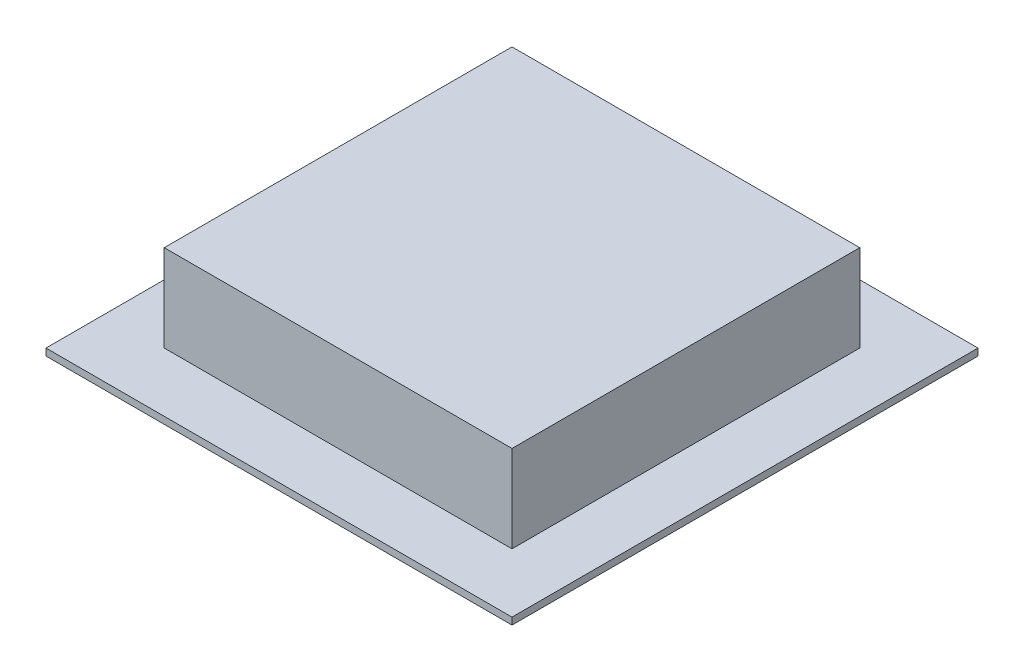
SolidWorks part; units mm, degrees
material "Default"
ref_plane "Front Plane" through (0, 0, 0) normal (0, 0, 1) x (1, 0, 0)
ref_plane "Top Plane" through (0, 0, 0) normal (0, 1, 0) x (1, 0, 0)
ref_plane "Right Plane" through (0, 0, 0) normal (1, 0, 0) x (0, 0, -1)
sketch "Sketch1" plane through (0, 0, 0) normal (0, 1, 0) x (1, 0, 0)
  line L1 (-85.09, 85.09) -> (85.09, 85.09)
  line L2 (-85.09, 85.09) -> (-85.09, -85.09)
  line L3 (-85.09, -85.09) -> (85.09, -85.09)
  line L4 (85.09, 85.09) -> (85.09, -85.09)
  point P4 (0, 85.09)
  point P6 (-85.09, 0)
  dimension "D1" = 170.18
  dimension "D2" = 170.18
extrude "Boss-Extrude1" add sketch "Sketch1" along normal blind 2.54
sketch "Sketch2" plane through (0, 2.54, 0) normal (0, 1, 0) x (1, 0, 0)
  line L1 (-63.5, 63.5) -> (63.5, 63.5)
  line L2 (-63.5, 63.5) -> (-63.5, -63.5)
  line L3 (-63.5, -63.5) -> (63.5, -63.5)
  line L4 (63.5, 63.5) -> (63.5, -63.5)
  point P4 (-63.5, 0)
  point P6 (0, 63.5)
  dimension "D1" = 127
  dimension "D2" = 127
extrude "Boss-Extrude2" add sketch "Sketch2" along normal blind 31.75
hole_wizard "Ø4.0mm Dowel Hole1" positions "Sketch3" profile "Sketch4" hole size "Ø4.0" standard "ANSI Metric"
sketch "Sketch3" plane through (0, 2.54, 0) normal (0, 1, 0) x (1, 0, 0)
  line L0 (-85.09, 85.09) -> (-85.09, -85.09) construction
  line L1 (85.09, 85.09) -> (-85.09, 85.09) construction
  point P0 (-80.01, 78.74)
  dimension "D1" = 5.08
  dimension "D2" = 6.35
sketch "Sketch4" plane through (-80.01, 2.54, -78.74) normal (1, 0, 0) x (0, 0, 1)
  line L0 (0, 0) -> (0, 13.9017)
  line L1 (0, 13.9017) -> (2, 12.7)
  line L2 (2, 12.7) -> (2, 0)
  line L5 (2, 0) -> (0, 0)
  line L10 (0, 13.9017) -> (-2, 12.7) construction
  line L11 (0, -6.35) -> (0, 107.95) construction
  dimension "Hole Dia." = 4
  dimension "Hole Depth" = 12.7
  dimension "Drill Angle" = 118
